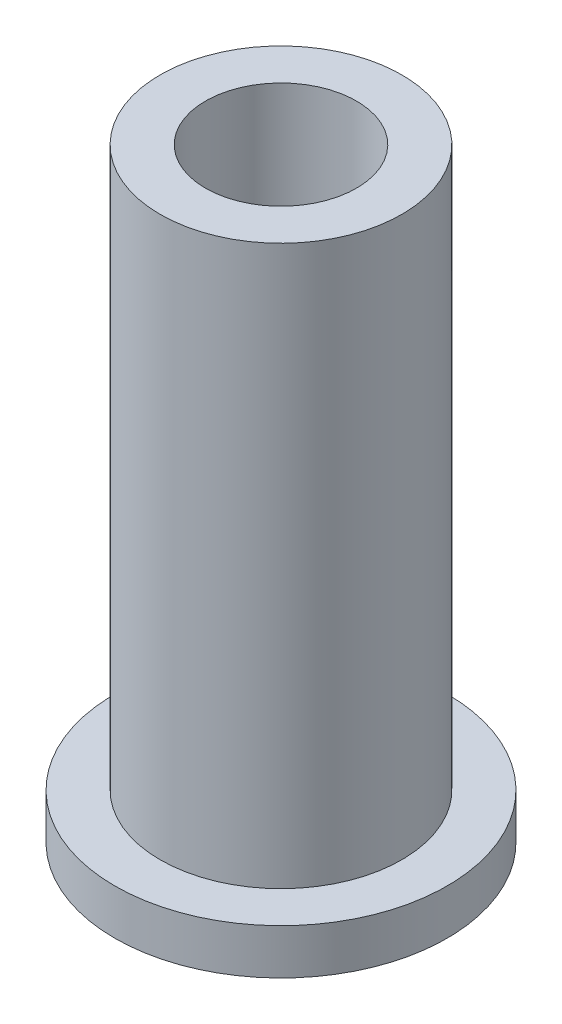
SolidWorks part; units mm, degrees
ref_plane "Front Plane" through (0, 0, 0) normal (0, 0, 1) x (1, 0, 0)
ref_plane "Top Plane" through (0, 0, 0) normal (0, 1, 0) x (1, 0, 0)
ref_plane "Right Plane" through (0, 0, 0) normal (1, 0, 0) x (0, 0, -1)
sketch "Sketch1" plane through (0, 0, 0) normal (0, 1, 0) x (1, 0, 0)
  circle A0 centre (0, 0) radius 11
  circle A1 centre (0, 0) radius 8
  circle A2 centre (0, 0) radius 5
  point P5 (0, 0)
  dimension "D1" = 10
  dimension "D2" = 16
  dimension "D3" = 22
extrude "Boss-Extrude2" add sketch "Sketch1" along normal blind 40 contours A1 | A2
sketch "Sketch4" plane through (0, 0, 0) normal (0, 1, 0) x (1, 0, 0)
  circle A0 centre (0, 0) radius 11
  circle A1 centre (0, 0) radius 8
  dimension "D1" = 22
  dimension "D2" = 16
extrude "Boss-Extrude4" add sketch "Sketch4" along normal blind 3
